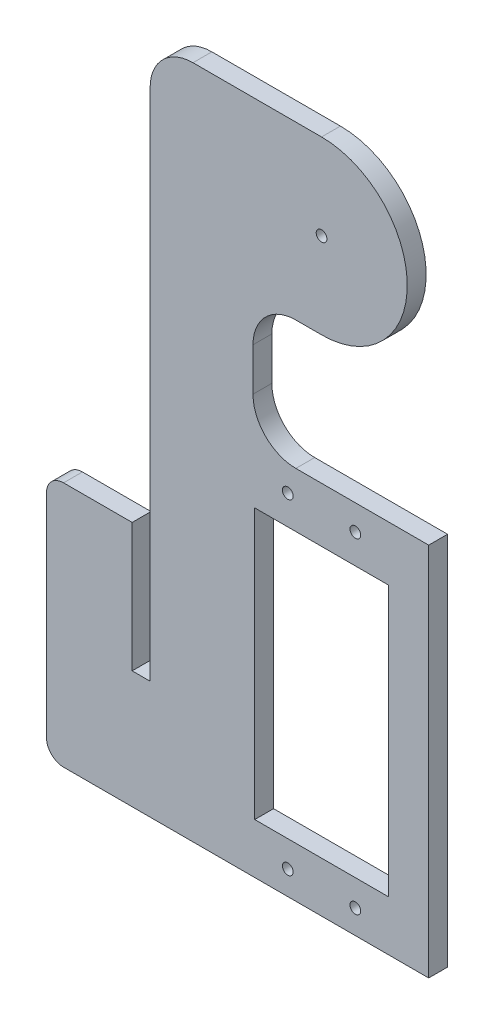
SolidWorks part; units mm, degrees
ref_plane "Front Plane" through (0, 0, 0) normal (0, 0, 1) x (1, 0, 0)
ref_plane "Top Plane" through (0, 0, 0) normal (0, 1, 0) x (1, 0, 0)
ref_plane "Right Plane" through (0, 0, 0) normal (1, 0, 0) x (0, 0, -1)
sketch "Sketch1" plane through (0, 0, 0) normal (0, 0, 1) x (1, 0, 0)
  line L1 (-5.842, 4.7342) -> (50.8, 4.7342)
  line L2 (-5.842, 4.7342) -> (-5.842, 41.2272)
  line L3 (-5.842, 41.2272) -> (6.858, 41.2272)
  line L4 (50.8, 4.7342) -> (50.8, 36.3432)
  line L5 (25.019, 52.1772) -> (44.831, 52.1772)
  line L6 (6.858, 41.2272) -> (6.858, 22.1772)
  line L7 (6.858, 22.1772) -> (9.525, 22.1772)
  line L8 (9.525, 38.1) -> (9.525, 22.1772)
  line L9 (25.019, 52.1772) -> (25.019, 12.1772)
  line L10 (9.525, 38.1) -> (9.525, 104.7272)
  line L11 (9.525, 104.7272) -> (34.925, 104.7272)
  line L12 (50.8, 36.3432) -> (50.8, 60.2848)
  line L13 (25.019, 12.1772) -> (44.831, 12.1772)
  line L14 (44.831, 52.1772) -> (44.831, 12.1772)
  line L15 (25.019, 52.1772) -> (44.831, 12.1772) construction
  line L16 (25.019, 12.1772) -> (44.831, 52.1772) construction
  line L17 (50.8, 60.2848) -> (24.765, 60.2848)
  line L21 (34.925, 79.3272) -> (24.765, 79.3272)
  line L22 (24.765, 60.2848) -> (24.765, 79.3272)
  circle A0 centre (34.925, 92.0272) radius 0.7937
  arc A1 (34.925, 79.3272) -> (34.925, 104.7272) centre (34.925, 92.0272) ccw
  circle A2 centre (29.9212, 8.2834) radius 0.7937
  circle A3 centre (39.9288, 8.2834) radius 0.7937
  circle A4 centre (29.9212, 56.518) radius 0.7937
  circle A5 centre (39.9288, 56.518) radius 0.7937
  point P11 (34.925, 32.1772)
  dimension "D17" = 12.7
  dimension "D10" = 13.8938
  dimension "D11" = 4.9022
  dimension "D15" = 34.3408
  dimension "D2" = 82.55
  dimension "D3" = 12.7
  dimension "D4" = 2.667
  dimension "D6" = 25.4
  dimension "D7" = 40
  dimension "D8" = 19.812
  dimension "D9" = 10
  dimension "D12" = 15.24
  dimension "D13" = 25.4
  dimension "D14" = 4.9022
  dimension "D18" = 25.4
extrude "Boss-Extrude1" add sketch "Sketch1" along normal blind 2.794
fillet "Fillet1" radius 6.35 2 edges at (24.765, 60.2848, 1.397) (24.765, 79.3272, 1.397)
fillet "Fillet2" radius 6.35 1 edges at (9.525, 104.7272, 1.397)
fillet "Fillet5" radius 2.54 2 edges at (-5.842, 41.2272, 1.397) (-5.842, 4.7342, 1.397)
